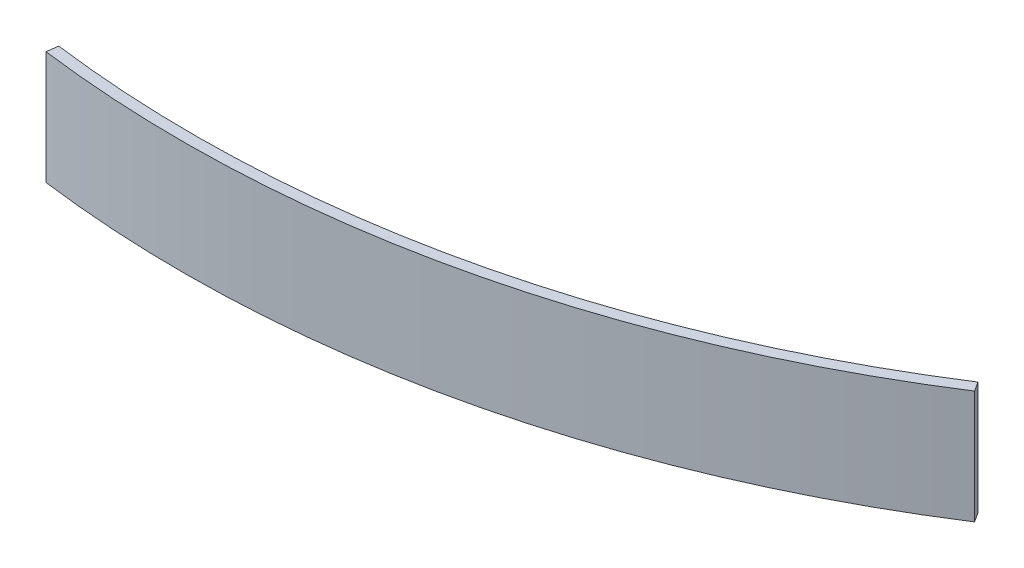
SolidWorks part; units mm, degrees
ref_plane "Front Plane" through (0, 0, 0) normal (0, 0, 1) x (1, 0, 0)
ref_plane "Top Plane" through (0, 0, 0) normal (0, 1, 0) x (1, 0, 0)
ref_plane "Right Plane" through (0, 0, 0) normal (1, 0, 0) x (0, 0, -1)
sketch "Sketch1" plane through (0, 0, 0) normal (0, 1, 0) x (1, 0, 0)
  line L0 (-128.6211, -991.6938) -> (-127.3349, -981.7769)
  line L1 (0, 0) -> (540.4918, -841.3493) construction
  line L2 (535.0869, -832.9358) -> (540.4918, -841.3493)
  line L3 (317.5596, -606.4047) -> (323.4643, -614.4753)
  line L4 (976.3361, -415.8026) -> (975.653, -425.7793)
  line L5 (372.9393, -580.531) -> (367.5344, -572.1175) construction
  line L6 (483.6464, -863.8207) -> (488.5317, -872.5461) construction
  line L8 (323.4643, -614.4753) -> (316.1266, -608.0335)
  line L9 (916.8147, -282.0837) -> (915.1536, -272.4619)
  arc A0 (-128.6211, -991.6938) -> (540.4918, -841.3493) centre (0, 0) ccw
  arc A1 (-127.3349, -981.7769) -> (535.0869, -832.9358) centre (0, 0) ccw
  point P1 (0, 0)
  dimension "D1" = 2000
  dimension "D2" = 1980
  dimension "D3" = 0
  dimension "D4" = 0
  dimension "D6" = 127.3349
  dimension "D12" = 0
  dimension "D13" = 60
extrude "Boss-Extrude8" add sketch "Sketch1" along normal blind 100 contours A1 L0 A0 L2
